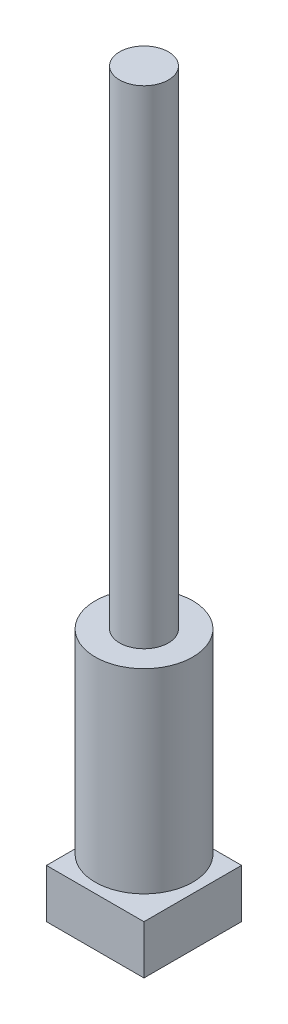
SolidWorks part; units mm, degrees
ref_plane "前视基准面" through (0, 0, 0) normal (0, 0, 1) x (1, 0, 0)
ref_plane "上视基准面" through (0, 0, 0) normal (0, 1, 0) x (1, 0, 0)
ref_plane "右视基准面" through (0, 0, 0) normal (1, 0, 0) x (0, 0, -1)
sketch "草图1" plane through (0, 0, 0) normal (0, 0, 1) x (1, 0, 0)
  line L1 (-25, 0) -> (-25, 500)
  line L2 (-25, 500) -> (0, 500)
  line L5 (0, 0) -> (0, 500)
  line L6 (-25, 0) -> (-50, 0)
  line L7 (-50, 0) -> (-50, -200)
  line L8 (-50, -200) -> (0, -200)
  line L9 (0, -200) -> (0, 0)
  dimension "D1" = 25
  dimension "D2" = 500
  dimension "D3" = 25
  dimension "D4" = 200
revolve "旋转1" add sketch "草图1" angle 360 about L5
ref_plane "基准面1" through (0, -210, 0) normal (0, -1, 0) x (-1, 0, 0)
sketch "草图2" plane through (0, -210, 0) normal (0, -1, 0) x (-1, 0, 0)
  line L0 (-50, 50.0444) -> (50, 50.0444)
  line L1 (-50, 50.0444) -> (-50, -50.0444)
  line L2 (50, 50.0444) -> (50, -50.0444)
  line L3 (-50, -50.0444) -> (50, -50.0444)
  line L4 (-50, 50.0444) -> (50, -50.0444) construction
  line L5 (50, 50.0444) -> (-50, -50.0444) construction
  point P1 (0, 0)
extrude "凸台-拉伸1" add sketch "草图2" along normal blind 50 separate body
